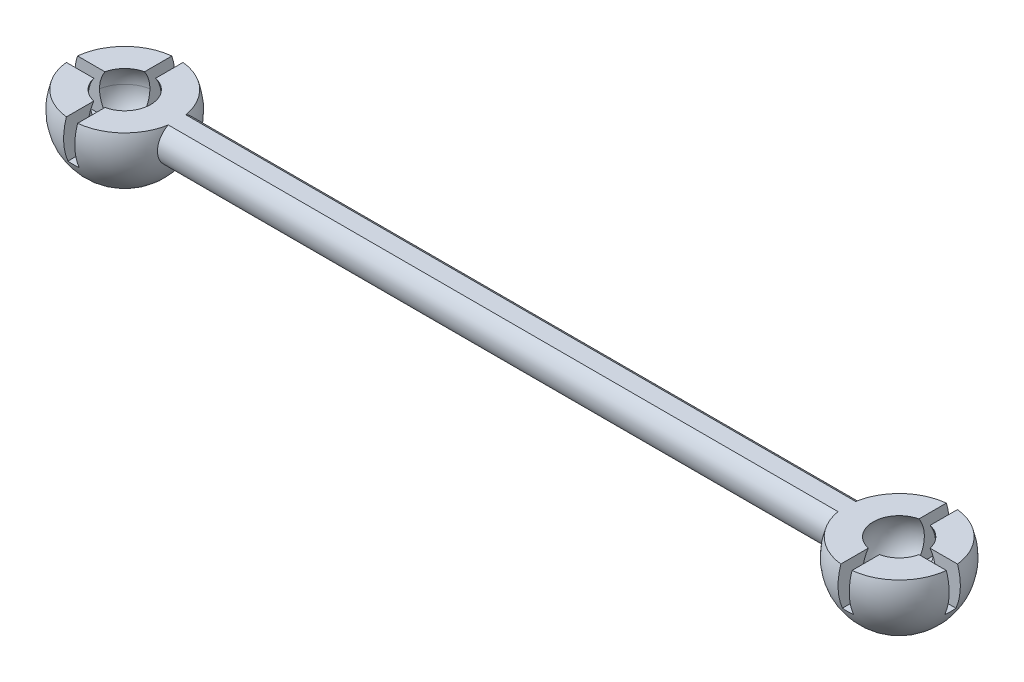
SolidWorks part; units mm, degrees
ref_plane "Front Plane" through (0, 0, 0) normal (0, 0, 1) x (1, 0, 0)
ref_plane "Top Plane" through (0, 0, 0) normal (0, 1, 0) x (1, 0, 0)
ref_plane "Right Plane" through (0, 0, 0) normal (1, 0, 0) x (0, 0, -1)
sketch "Sketch1" plane through (0, 0, 0) normal (0, 1, 0) x (1, 0, 0)
  line L0 (-79.3675, 0) -> (79.3675, 0)
  line L1 (0, 0) -> (0, 3.5)
  line L2 (60, 3.5) -> (-60, 3.5)
  arc A0 (-60, 3.5) -> (-79.3675, 0) centre (-69.3675, 0) ccw
  arc A1 (-74.9675, 0) -> (-63.7675, 0) centre (-69.3675, 0) cw
  arc A2 (74.9675, 0) -> (63.7675, 0) centre (69.3675, 0) ccw
  arc A3 (60, 3.5) -> (79.3675, 0) centre (69.3675, 0) cw
  point P3 (0, 0)
  point P6 (0, 0)
  point P10 (0, 0)
  point P11 (0, 0)
  point P12 (0, 0)
  point P13 (0, 0)
  point P14 (0, 0)
  point P15 (-34.7978, 5.2778)
  point P16 (0, 0)
  point P17 (0, 0)
  point P18 (0, 0)
  point P19 (-29.6867, 2.1667)
  point P20 (0, 0)
  point P21 (0, 0)
  point P22 (0, 0)
  point P23 (-42.6422, 0)
  point P24 (-50.1089, 0)
  point P25 (-33.3089, 3.5)
  point P26 (-56.5089, 0)
  point P27 (-24.9089, 3.5)
  point P28 (-37.8422, 0)
  point P29 (0, 0)
  point P30 (-49.4422, 0)
  point P31 (-61.1756, 0)
  point P32 (-56.9089, 0)
  point P33 (-19.5756, 0)
  point P34 (-45.0422, 0)
  point P35 (-41.0422, 0)
  point P36 (-34.9089, 3.5)
  dimension "D3" = 10
  dimension "D4" = 5.6
  dimension "D1" = 3.5
  dimension "D2" = 60
revolve "Revolve1" add sketch "Sketch1" angle 360 about L0
ref_plane "Plane1" through (-60, 0, 0) normal (1, 0, 0) x (0, 0, -1)
sketch "Sketch2" plane through (-60, 0, 0) normal (1, 0, 0) x (0, 0, -1)
  line L0 (-9.4989, 3.1258) -> (9.4989, 3.1258)
  circle A0 centre (0, 0) radius 10 construction
  arc A1 (9.4989, 3.1258) -> (-9.4989, 3.1258) centre (0, 0) ccw
  point P5 (0, 3.6947)
  point P6 (0, 0)
  point P7 (0, 0)
  point P8 (0, 0)
extrude "Cut-Extrude1" cut sketch "Sketch2" against normal mid plane 500
ref_plane "Plane3" through (0, 3.1258, 0) normal (0, 1, 0) x (1, 0, 0)
sketch "Sketch3" plane through (0, 3.1258, 0) normal (0, 1, 0) x (1, 0, 0)
  line L0 (73.9051, 1) -> (80.6431, 1)
  line L1 (80.6431, 1) -> (80.6431, -1)
  line L2 (80.6431, -1) -> (73.9051, -1)
  line L3 (70.3675, -11.2756) -> (68.3675, -11.2756)
  line L4 (68.3675, -11.2756) -> (68.3675, -4.5376)
  line L5 (70.3675, -4.5376) -> (70.3675, -11.2756)
  line L7 (90.6321, 0) -> (52.6885, 0) construction
  line L10 (68.3675, 11.2756) -> (70.3675, 11.2756)
  line L11 (70.3675, 11.2756) -> (70.3675, 4.5376)
  line L12 (68.3675, 4.5376) -> (68.3675, 11.2756)
  line L13 (69.3675, 0) -> (68.3951, 0) construction
  line L14 (69.3675, 0) -> (69.3675, 0.9724) construction
  line L15 (64.8299, -1) -> (58.0919, -1) [skipped]
  line L16 (58.0919, 1) -> (64.8299, 1) [skipped]
  line L17 (58.0919, -1) -> (58.0919, 1) [skipped]
  line L18 (0, 29.3257) -> (0, -28.6095) construction
  line L19 (-70.3675, -11.2756) -> (-68.3675, -11.2756)
  line L20 (-68.3675, -11.2756) -> (-68.3675, -4.5376)
  line L21 (-70.3675, -4.5376) -> (-70.3675, -11.2756)
  line L22 (-80.6431, -1) -> (-73.9051, -1)
  line L23 (-73.9051, 1) -> (-80.6431, 1)
  line L24 (-80.6431, 1) -> (-80.6431, -1)
  line L25 (-68.3675, 11.2756) -> (-70.3675, 11.2756)
  line L26 (-68.3675, 4.5376) -> (-68.3675, 11.2756)
  line L27 (-70.3675, 11.2756) -> (-70.3675, 4.5376)
  circle A0 centre (69.3675, 0) radius 4.6465 construction
  arc A2 (73.9051, 1) -> (73.9051, -1) centre (68.3951, 0) cw
  arc A3 (70.3675, -4.5376) -> (68.3675, -4.5376) centre (69.3675, 0.9724) cw
  arc A5 (68.3675, 4.5376) -> (70.3675, 4.5376) centre (69.3675, -0.9724) cw
  arc A6 (64.8299, -1) -> (64.8299, 1) centre (70.3399, 0) cw [skipped]
  arc A7 (-70.3675, -4.5376) -> (-68.3675, -4.5376) centre (-69.3675, 0.9724) ccw
  arc A8 (-73.9051, 1) -> (-73.9051, -1) centre (-68.3951, 0) ccw
  arc A9 (-68.3675, 4.5376) -> (-70.3675, 4.5376) centre (-69.3675, -0.9724) ccw
  dimension "D1" = 5.6
  dimension "D2" = 2
  dimension "D3" = 1
  dimension "D5" = 90
  dimension "D4" = 4
extrude "Cut-Extrude2" cut sketch "Sketch3" against normal blind 7
